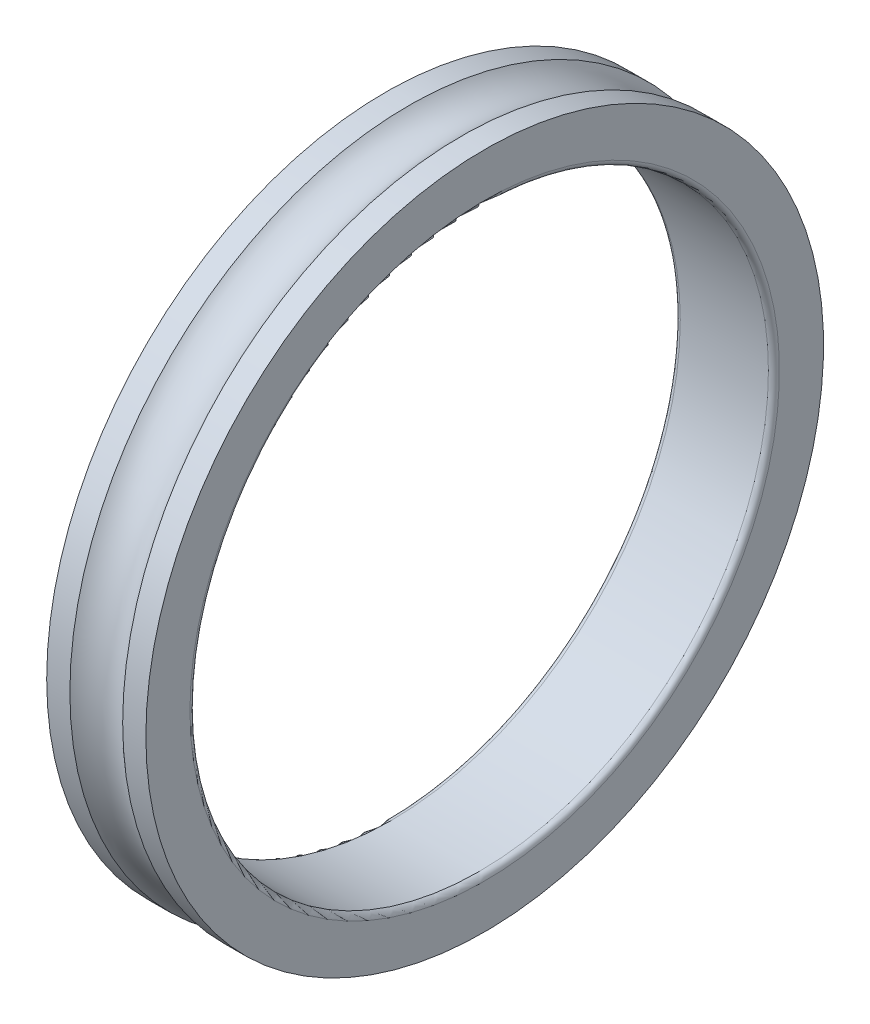
SolidWorks part; units mm, degrees
ref_plane "Piano frontale" through (0, 0, 0) normal (0, 0, 1) x (1, 0, 0)
ref_plane "Piano superiore" through (0, 0, 0) normal (0, 1, 0) x (1, 0, 0)
ref_plane "Piano destro" through (0, 0, 0) normal (1, 0, 0) x (0, 0, -1)
ref_plane "Piano1" through (0, 0, 0) normal (0, 0, 1) x (1, 0, 0)
sketch "Schizzo1" plane through (0, 0, 0) normal (0, 0, 1) x (1, 0, 0)
  line L0 (1, 52.5) -> (17, 52.5)
  line L1 (18, 53.5) -> (18, 61.5)
  line L2 (18, 61.5) -> (13.7916, 61.5)
  line L3 (4.2084, 61.5) -> (0, 61.5)
  line L4 (0, 61.5) -> (0, 53.5)
  line L5 (50, 0) -> (-50, 0) construction
  arc A0 (0, 53.5) -> (1, 52.5) centre (1, 53.5) ccw
  arc A1 (17, 52.5) -> (18, 53.5) centre (17, 53.5) ccw
  arc A2 (13.7916, 61.5) -> (4.2084, 61.5) centre (9, 66.25) cw
revolve "Rivoluzione1" add sketch "Schizzo1" angle 360 about L5
